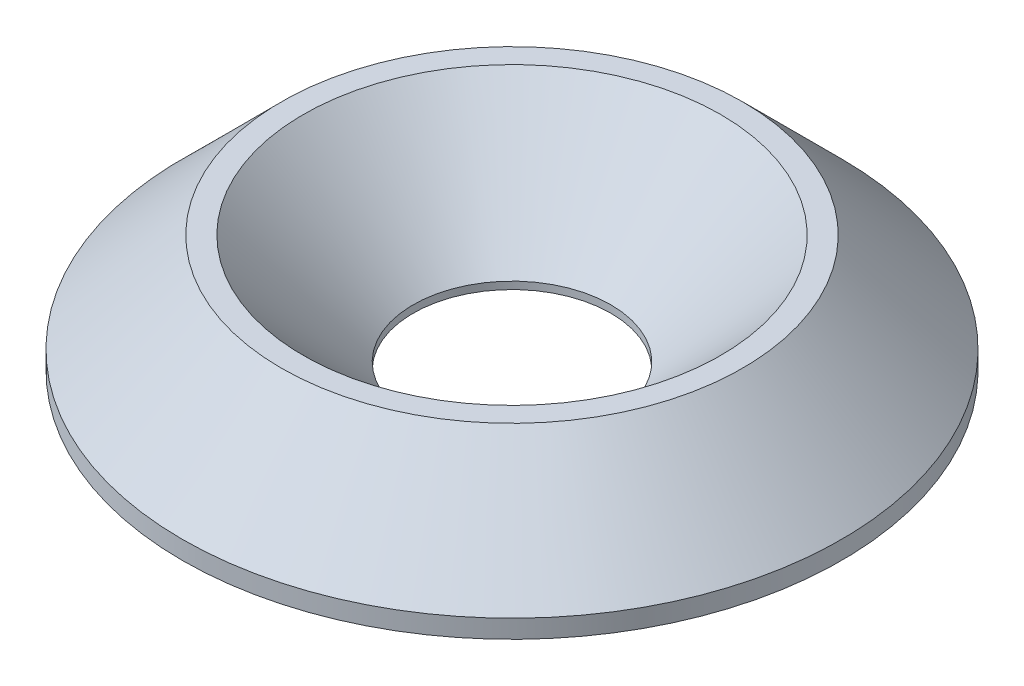
SolidWorks part; units mm, degrees
material "Acier allié"
ref_plane "Plan de face" through (0, 0, 0) normal (0, 0, 1) x (1, 0, 0)
ref_plane "Plan de dessus" through (0, 0, 0) normal (0, 1, 0) x (1, 0, 0)
ref_plane "Plan de droite" through (0, 0, 0) normal (1, 0, 0) x (0, 0, -1)
sketch "Esquisse1" plane through (0, 0, 0) normal (0, 0, 1) x (1, 0, 0)
  line L0 (1.35, 0) -> (4.5, 0)
  line L1 (4.5, 0) -> (4.5, 0.25)
  line L2 (4.5, 0.25) -> (3.15, 1.6)
  line L3 (3.15, 1.6) -> (2.85, 1.6)
  line L4 (2.85, 1.6) -> (1.35, 0.1)
  line L5 (1.35, 0.1) -> (1.35, 0)
  line L7 (0, 0) -> (0, 1.6) construction
  dimension "D1" = 2.7
  dimension "D2" = 45
  dimension "D3" = 5.7
  dimension "D4" = 6.3
  dimension "D5" = 9
  dimension "D6" = 1.6
  dimension "D7" = 45
revolve "Révolution1" add sketch "Esquisse1" angle 360 about L7
